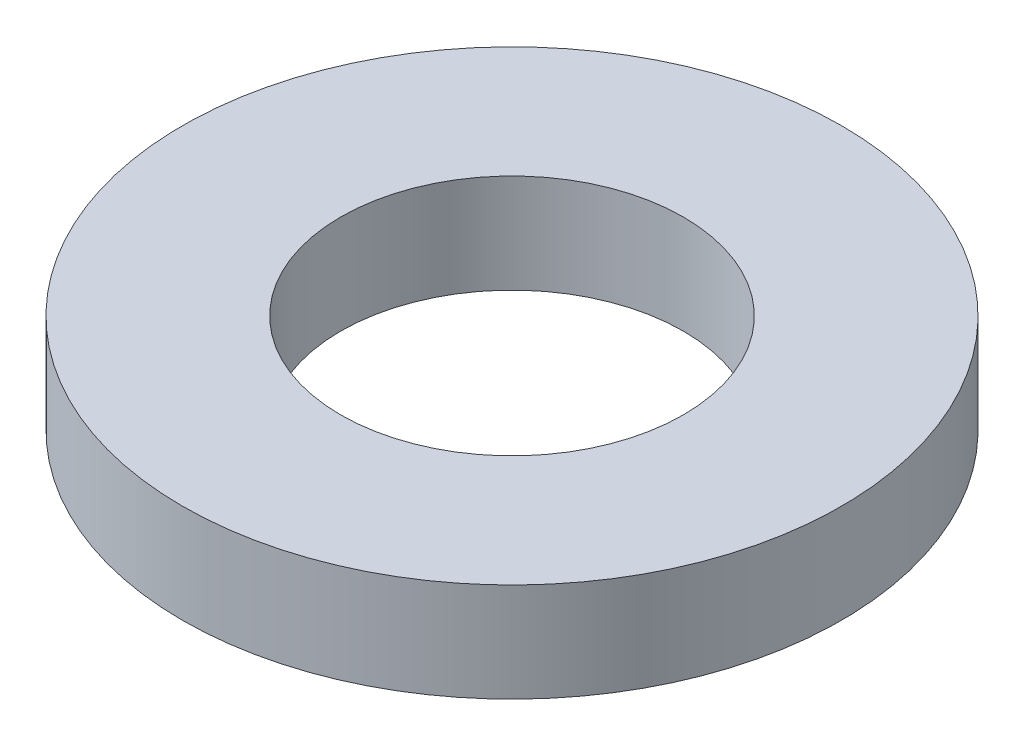
SolidWorks part; units mm, degrees
material "6061 合金"
ref_plane "前视基准面" through (0, 0, 0) normal (0, 0, 1) x (1, 0, 0)
ref_plane "上视基准面" through (0, 0, 0) normal (0, 1, 0) x (1, 0, 0)
ref_plane "右视基准面" through (0, 0, 0) normal (1, 0, 0) x (0, 0, -1)
sketch "草图1" plane through (0, 0, 0) normal (0, 1, 0) x (1, 0, 0)
  circle A0 centre (0, 0) radius 5
  circle A1 centre (0, 0) radius 2.6
  dimension "D1" = 5.2
  dimension "D2" = 10
extrude "凸台-拉伸1" add sketch "草图1" along normal blind 1.5
